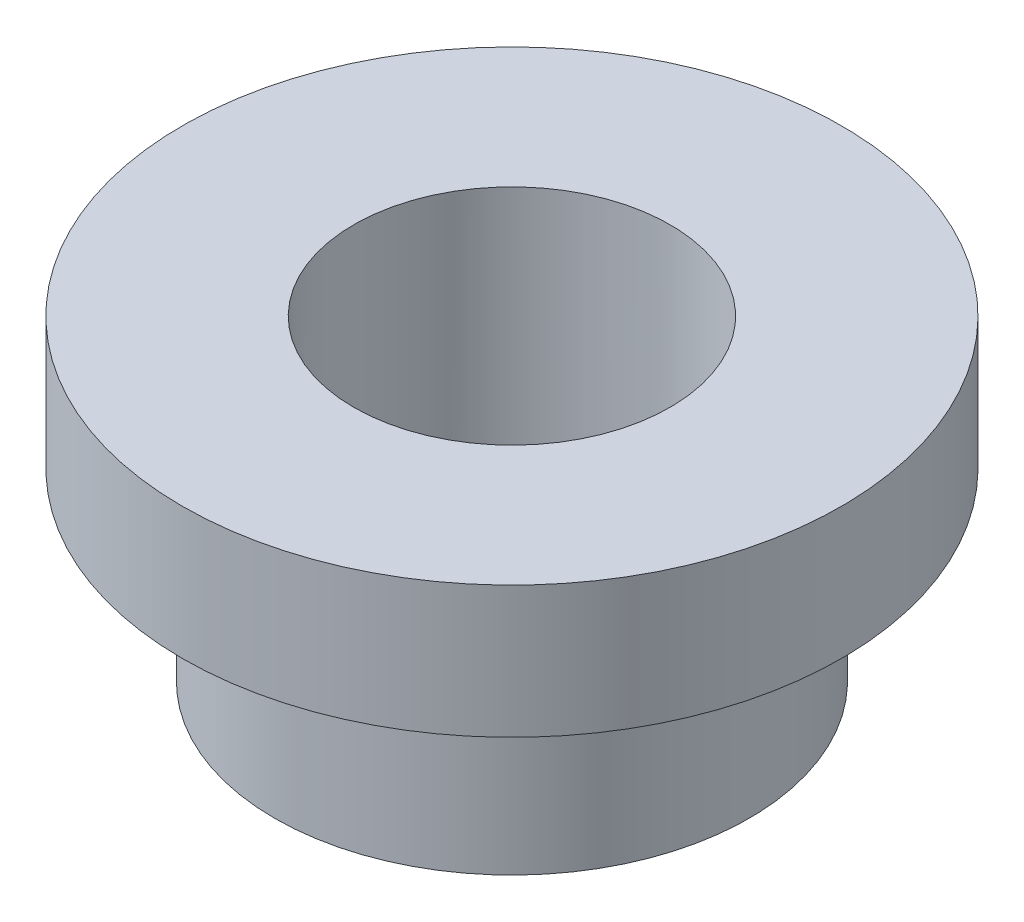
SolidWorks part; units mm, degrees
ref_plane "Front Plane" through (0, 0, 0) normal (0, 0, 1) x (1, 0, 0)
ref_plane "Top Plane" through (0, 0, 0) normal (0, 1, 0) x (1, 0, 0)
ref_plane "Right Plane" through (0, 0, 0) normal (1, 0, 0) x (0, 0, -1)
sketch "Sketch1" plane through (0, 0, 0) normal (0, 1, 0) x (1, 0, 0)
  circle A0 centre (0, 0) radius 1.25
  circle A1 centre (0, 0) radius 0.6
extrude "Boss-Extrude1" add sketch "Sketch1" against normal blind 0.5
sketch "Sketch2" plane through (0, -0.5, 0) normal (0, -1, 0) x (1, 0, 0)
  circle A0 centre (0, 0) radius 0.6
  circle A1 centre (0, 0) radius 0.9
extrude "Boss-Extrude2" add sketch "Sketch2" along normal blind 0.7
